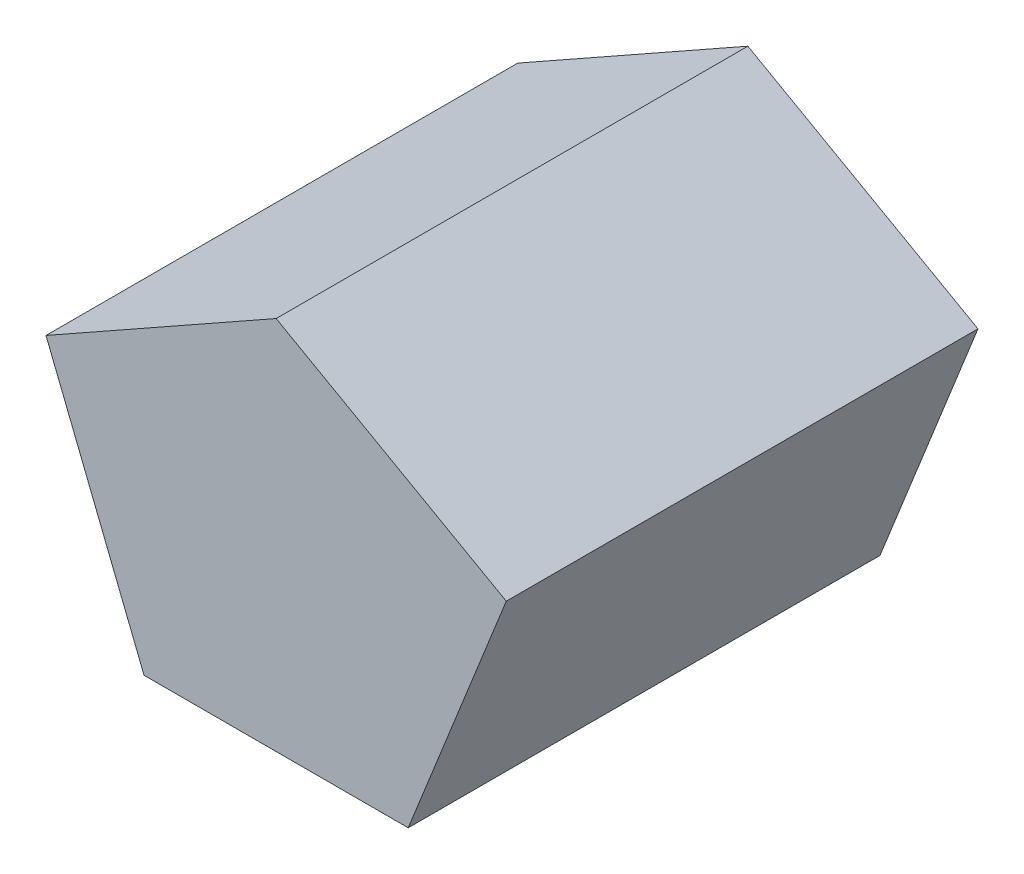
SolidWorks part; units mm, degrees
ref_plane "Alzado" through (0, 0, 0) normal (0, 0, 1) x (1, 0, 0)
ref_plane "Planta" through (0, 0, 0) normal (0, 1, 0) x (1, 0, 0)
ref_plane "Vista lateral" through (0, 0, 0) normal (1, 0, 0) x (0, 0, -1)
sketch "Croquis2" plane through (0, 0, 0) normal (0, 0, 1) x (1, 0, 0)
  line L0 (0.3706, 31.3206) -> (-24.0217, 17.5723)
  line L1 (-24.0217, 17.5723) -> (-13.6294, -8.4277)
  line L2 (-13.6294, -8.4277) -> (14.3706, -8.4277)
  line L3 (14.3706, -8.4277) -> (24.7629, 17.5723)
  line L4 (24.7629, 17.5723) -> (0.3706, 31.3206)
  dimension "D1" = 28
  dimension "D2" = 28
  dimension "D3" = 28
  dimension "D4" = 28
  dimension "D5" = 28
  dimension "D6" = 26
  dimension "D7" = 26
extrude "Saliente-Extruir1" add sketch "Croquis2" along normal blind 50
sketch "Croquis3" plane through (0, 0, 0) normal (0, 0, -1) x (-1, 0, 0)
  circle A0 centre (0, 6.6205) radius 5
  dimension "D1" = 10
extrude "Cortar-Extruir1" cut sketch "Croquis3" against normal blind 10
